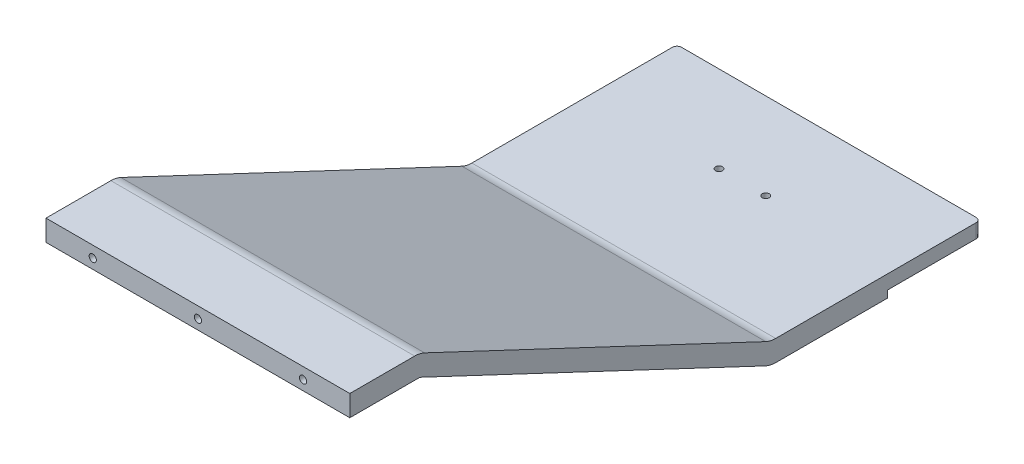
SolidWorks part; units mm, degrees
ref_plane "前视基准面" through (0, 0, 0) normal (0, 0, 1) x (1, 0, 0)
ref_plane "上视基准面" through (0, 0, 0) normal (0, 1, 0) x (1, 0, 0)
ref_plane "右视基准面" through (0, 0, 0) normal (1, 0, 0) x (0, 0, -1)
other "Configuration Table"
sketch "草图1" plane through (0, 0, 0) normal (0, 0, 1) x (1, 0, 0)
  line L0 (0, 0) -> (0, 79)
  line L1 (0, 79) -> (79, 79)
  line L2 (79, 79) -> (79, 70)
  line L3 (79, 70) -> (9, 70)
  line L4 (9, 70) -> (9, 0)
  line L5 (9, 0) -> (0, 0)
  dimension "D1" = 9
  dimension "D2" = 9
  dimension "D3" = 70
  dimension "D4" = 70
ref_plane "基准面1" through (0, 0, 150) normal (0, 0, 1) x (1, 0, 0)
sketch "草图2" plane through (0, 0, 150) normal (0, 0, 1) x (1, 0, 0)
  line L0 (0, 79) -> (-70.7107, 149.7107) construction
  line L1 (0, 0) -> (0, 79) construction
  line L2 (-70.7107, 149.7107) -> (-70.7107, 0)
  line L3 (-70.7107, 0) -> (-61.7107, 0)
  line L4 (-61.7107, 0) -> (-61.7107, 140.7107)
  line L5 (-61.7107, 140.7107) -> (79, 140.7107)
  line L6 (79, 140.7107) -> (79, 149.7107)
  line L7 (79, 149.7107) -> (-70.7107, 149.7107)
  line L8 (0, 0) -> (0, 79) construction
  line L9 (0, 79) -> (79, 79) construction
  dimension "D1" = 135
  dimension "D2" = 9
  dimension "D3" = 100
  dimension "D4" = 79
loft "放样1" add profiles "草图1", "草图2"
sketch "草图4" plane through (0, 0, 0) normal (0, 0, -1) x (-1, 0, 0)
  line L7 (-9, 0) -> (0, 0)
  line L8 (0, 0) -> (0, 79)
  line L9 (0, 79) -> (-79, 79)
  line L10 (-79, 79) -> (-79, 70)
  line L11 (-79, 70) -> (-77.7656, 70)
  line L12 (-77.7656, 70) -> (-9, 70)
  line L13 (-9, 70) -> (-9, 0)
  line L14 (-9, 0) -> (0, 0)
  line L15 (0, 0) -> (0, 79)
  line L16 (0, 79) -> (-79, 79)
  line L17 (-79, 79) -> (-79, 70)
  line L18 (-79, 70) -> (-77.7656, 70)
  line L19 (-77.7656, 70) -> (-9, 70)
  line L20 (-9, 70) -> (-9, 0)
  dimension "D1" = 0
extrude "凸台-拉伸1" add sketch "草图4" along normal blind 50
sketch "草图9" plane through (0, 0, -50) normal (0, 0, -1) x (-1, 0, 0)
  line L0 (-9, 70) -> (-9, 0) construction
  line L1 (-9, 70) -> (-55, 70)
  line L2 (-9, 70) -> (-9, 30)
  line L3 (-15, 64) -> (-55, 64)
  line L4 (-55, 70) -> (-55, 64)
  line L6 (-15, 64) -> (-15, 30)
  line L7 (-15, 30) -> (-9, 30)
  dimension "D1" = 6
  dimension "D2" = 46
  dimension "D3" = 6
  dimension "D4" = 40
extrude "凸台-拉伸3" add sketch "草图9" against normal blind 6
fillet "圆角1" radius 10 7 edges
sketch "草图11" plane through (0, 0, -44) normal (0, 0, 1) x (1, 0, 0)
  circle A0 centre (12, 45) radius 1.55
  circle A1 centre (12, 65) radius 1.55
  circle A2 centre (30, 67) radius 1.55
  circle A3 centre (50, 67) radius 1.55
  dimension "D1" = 3.1
extrude "切除-拉伸1" cut sketch "草图11" against normal through all
sketch "草图12" plane through (0, 0, -50) normal (0, 0, -1) x (-1, 0, 0)
  line L0 (0, 19) -> (0, 0)
  line L1 (0, 0) -> (0, 69) construction
  line L2 (0, 0) -> (-6, 0)
  line L3 (-9, 0) -> (0, 0) construction
  line L5 (-6, 0) -> (-6, 19)
  line L6 (0, 19) -> (-6, 19)
  line L7 (-2.9289, 76.0711) -> (-93.7798, -14.7798) construction
  line L8 (0, 0) -> (0, 69) construction
  line L9 (-60, 79) -> (-60, 73)
  line L10 (-79, 73) -> (-60, 73)
  line L11 (-79, 79) -> (-79, 73)
  line L12 (-60, 79) -> (-79, 79)
  arc A0 (0, 69) -> (-10, 79) centre (-10, 69) ccw construction
  dimension "D1" = 19
  dimension "D2" = 6
  dimension "D3" = 45
extrude "凸台-拉伸4" add sketch "草图12" along normal blind 40
fillet "圆角2" radius 2 9 edges at (3, 0, -90) (3, 19, -90) (9, 30, -47) (15, 30, -47) (15, 64, -47) (55, 70, -47) (55, 64, -47) (79, 76, -90) (60, 76, -90)
sketch "草图13" plane through (79, 0, 0) normal (1, 0, 0) x (0, 0, -1)
  line L0 (90, 79) -> (88, 79) construction
  line L1 (90, 79) -> (90, 73) construction
  line L9 (50, 73) -> (88, 73)
  line L10 (88, 73) -> (88, 79)
  line L11 (88, 79) -> (2.2389, 79)
  line L12 (-2.0251, 79.9547) -> (-150, 149.7107)
  line L13 (-150, 149.7107) -> (-150, 149.2162)
  line L14 (-150, 149.2162) -> (-150, 140.7107)
  line L15 (-150, 140.7107) -> (-2.0251, 70.9547)
  line L16 (2.2389, 70) -> (50, 70)
  line L17 (50, 70) -> (50, 73)
  line L18 (50, 73) -> (90, 73)
  line L19 (90, 73) -> (90, 79)
  line L20 (90, 79) -> (2.2389, 79)
  line L21 (-2.0251, 79.9547) -> (-150, 149.7107)
  line L22 (-150, 149.7107) -> (-150, 149.2162)
  line L23 (-150, 149.2162) -> (-150, 140.7107)
  line L24 (-150, 140.7107) -> (-2.0251, 70.9547)
  line L25 (2.2389, 70) -> (50, 70)
  line L26 (50, 70) -> (50, 73)
  arc A2 (-2.0251, 79.9547) -> (2.2389, 79) centre (2.2389, 89) ccw
  arc A3 (-2.0251, 70.9547) -> (2.2389, 70) centre (2.2389, 80) ccw
  arc A4 (-2.0251, 79.9547) -> (2.2389, 79) centre (2.2389, 89) ccw
  arc A5 (-2.0251, 70.9547) -> (2.2389, 70) centre (2.2389, 80) ccw
  dimension "D1" = 0
extrude "凸台-拉伸5" add sketch "草图13" along normal blind 130 separate body
delete or keep bodies "实体-删除/保留 1" type delete bodies bodies 112
sketch "草图14" plane through (0, 0, 150) normal (0, 0, 1) x (1, 0, 0)
  line L4 (79, 149.7107) -> (79, 140.7107)
  line L5 (79, 140.7107) -> (209, 140.7107)
  line L6 (209, 140.7107) -> (209, 149.7107)
  line L7 (209, 149.7107) -> (79, 149.7107)
  line L8 (79, 149.7107) -> (79, 140.7107)
  line L9 (79, 140.7107) -> (209, 140.7107)
  line L10 (209, 140.7107) -> (209, 149.7107)
  line L11 (209, 149.7107) -> (79, 149.7107)
  dimension "D1" = 0
extrude "凸台-拉伸6" add sketch "草图14" along normal blind 30
sketch "草图15" plane through (0, 0, 180) normal (0, 0, 1) x (1, 0, 0)
  line L0 (79, 149.7107) -> (79, 140.7107) construction
  line L1 (79, 140.7107) -> (209, 140.7107) construction
  circle A0 centre (99, 144.8907) radius 1.55
  circle A1 centre (144, 144.8907) radius 1.55
  circle A2 centre (189, 144.8907) radius 1.55
  dimension "D1" = 3.1
  dimension "D2" = 20
  dimension "D3" = 4.18
  dimension "D5" = 45
  dimension "D4" = 3
extrude "切除-拉伸2" cut sketch "草图15" against normal blind 5
fillet "圆角3" radius 2 2 edges at (79, 76, -90) (209, 76, -90)
sketch "草图16" plane through (0, 73, 0) normal (0, -1, 0) x (1, 0, 0)
  line L1 (144, 180) -> (144, 82.7932) construction
  line L2 (79, 180) -> (209, 180) construction
  line L3 (209, -50) -> (79, -50) construction
  circle A0 centre (134, -53) radius 1.5
  circle A1 centre (154, -53) radius 1.5
  dimension "D1" = 3
  dimension "D2" = 3
  dimension "D3" = 20
extrude "切除-拉伸3" cut sketch "草图16" against normal through all
fillet "圆角4" radius 10 1 edges at (144, 149.7107, 150)
